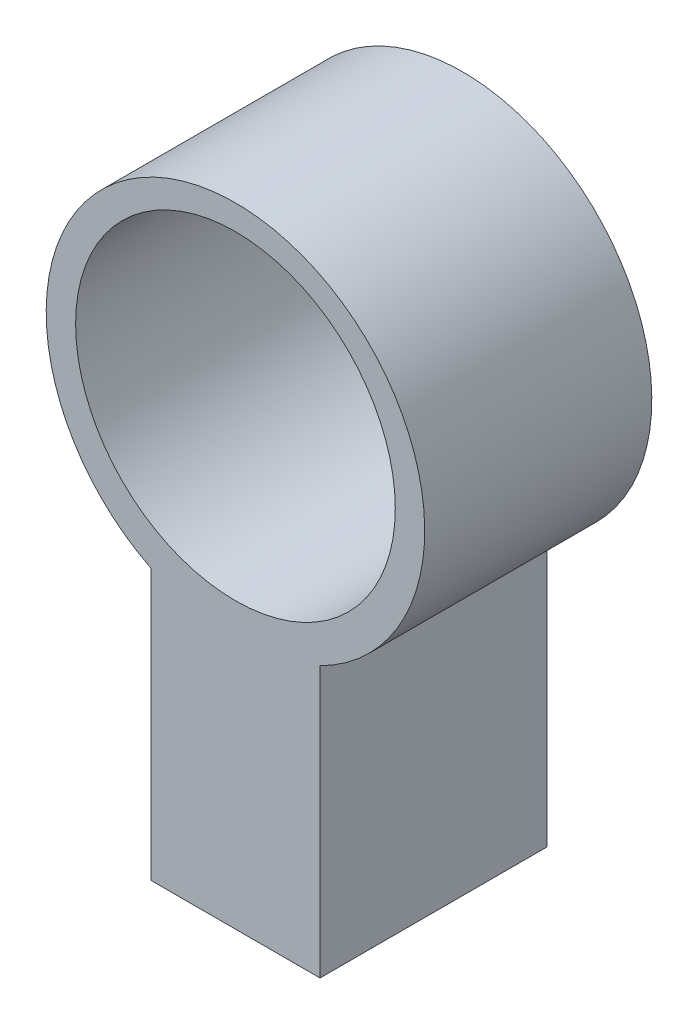
SolidWorks part; units mm, degrees
ref_plane "Plano frontal" through (0, 0, 0) normal (0, 0, 1) x (1, 0, 0)
ref_plane "Plano superior" through (0, 0, 0) normal (0, 1, 0) x (1, 0, 0)
ref_plane "Plano direito" through (0, 0, 0) normal (1, 0, 0) x (0, 0, -1)
sketch "Esboço1" plane through (0, 0, 0) normal (0, 0, 1) x (1, 0, 0)
  line L0 (0, 0) -> (0, 21.4353)
  line L1 (0, 0) -> (13.4061, 0)
  line L2 (13.4061, 0) -> (13.4061, 21.4353)
  arc A0 (13.4061, 21.4353) -> (0, 21.4353) centre (6.7031, 34.8543) ccw
  dimension "D1" = 15
extrude "Ressalto-extrusão1" add sketch "Esboço1" along normal blind 18
sketch "Esboço3" plane through (0, 0, 18) normal (0, 0, 1) x (1, 0, 0)
  circle A0 centre (6.7031, 35.2101) radius 12.668
extrude "Corte-extrusão2" cut sketch "Esboço3" against normal through all
